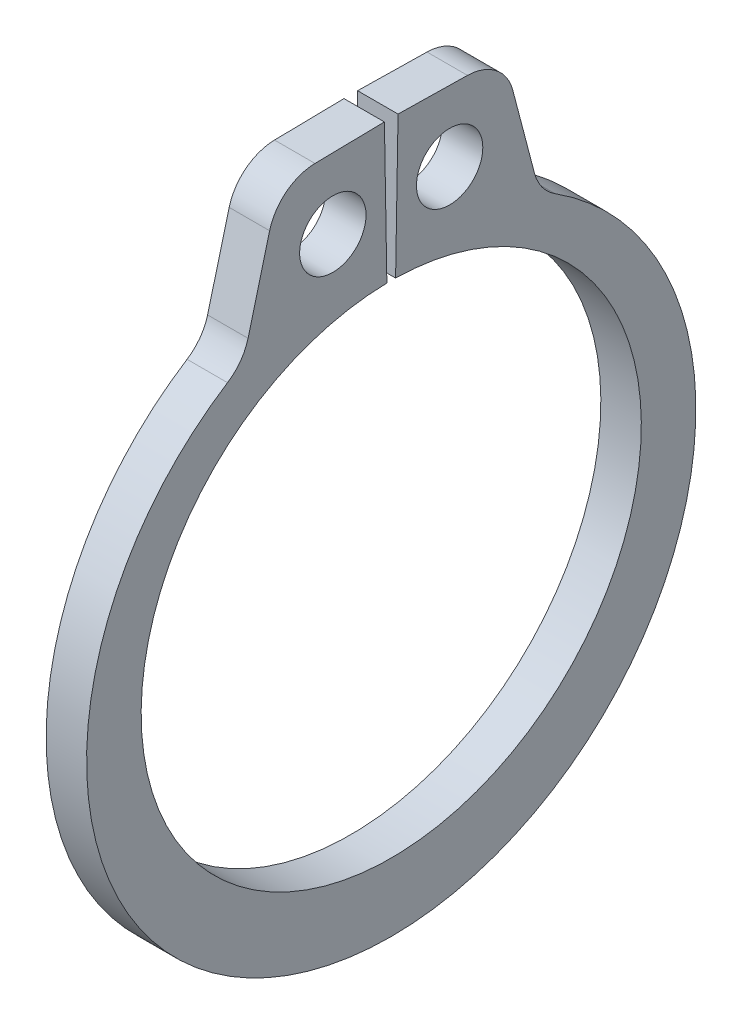
SolidWorks part; units mm, degrees
material "Cast Carbon Steel"
ref_plane "Front" through (0, 0, 0) normal (0, 0, 1) x (1, 0, 0)
ref_plane "Top" through (0, 0, 0) normal (0, 1, 0) x (1, 0, 0)
ref_plane "Right" through (0, 0, 0) normal (1, 0, 0) x (0, 0, -1)
sketch "Sketch1" plane through (0, 0, 0) normal (1, 0, 0) x (0, 0, -1)
  line L0 (0, 0) -> (0, 3.9243) construction
  line L1 (-0.0685, 3.9237) -> (-0.1071, 6.1332)
  line L2 (0.1071, 6.1332) -> (1.7642, 6.1042)
  line L3 (1.7642, 6.1042) -> (2.3243, 3.9666)
  line L4 (0.0685, 3.9237) -> (0.1071, 6.1332)
  line L5 (-0.1071, 6.1332) -> (-1.7642, 6.1042)
  line L6 (-1.7642, 6.1042) -> (-2.3243, 3.9666)
  line L7 (-2.3243, 3.9666) -> (-1.984, 3.3859) construction
  line L8 (2.3243, 3.9666) -> (1.984, 3.3859) construction
  line L9 (0, -3.9243) -> (0, -4.9911) construction
  line L10 (-1.7642, 6.1042) -> (-0.0685, 3.9237) construction
  line L11 (0, 3.9243) -> (0, 6.1341) construction
  line L12 (-3.9243, 0) -> (3.9243, 0) construction
  circle A0 centre (0, 0) radius 3.9243 construction
  arc A1 (-0.0685, 3.9237) -> (0.0685, 3.9237) centre (0, 0) ccw
  circle A3 centre (0, 0) radius 7.112 construction
  circle A4 centre (-0.9163, 5.014) radius 0.5207
  circle A5 centre (0.9163, 5.014) radius 0.5207
  arc A6 (-2.3243, 3.9666) -> (2.3243, 3.9666) centre (0, -0.2107) ccw
  point P0 (0, -4.9911)
  dimension "A" = 7.8486
  dimension "D2" = 1.6573
  dimension "L" = 14.224
  dimension "Hole" = 1.0414
  dimension "Smin" = 0.6731
  dimension "Smax" = 1.0668
  dimension "H" = 2.2098
  dimension "Angle" = 1
extrude "Extrude1" add sketch "Sketch1" along normal mid plane 0.635
fillet "Fillet1" radius 0.7493 4 edges at (0, 3.9666, 2.3243) (0, 3.9666, -2.3243) (0, 6.1042, 1.7642) (0, 6.1042, -1.7642)
sketch "Sketch2" plane through (0, 0, 0) normal (0, 0, 1) x (1, 0, 0)
  line L0 (-3.5433, 0) -> (9.1567, 0)
  line L1 (9.1567, 0) -> (9.1567, -4.3688)
  line L2 (-0.3683, -4.3688) -> (-3.2512, -4.3688)
  line L3 (9.1567, -4.3688) -> (0.3683, -4.3688)
  line L4 (0.3683, -4.3688) -> (0.3683, -4.0767)
  line L5 (0.3683, -4.0767) -> (-0.3683, -4.0767)
  line L6 (-0.3683, -4.0767) -> (-0.3683, -4.3688)
  line L7 (-0.3683, -4.3688) -> (-3.5433, -4.3688) construction
  line L8 (-3.5433, -4.3688) -> (-3.5433, 0) construction
  line L9 (9.1567, 0) -> (76.391, 0) construction
  line L10 (-3.2512, -4.3688) -> (-3.5433, -4.0767)
  line L11 (-3.5433, -4.0767) -> (-3.5433, 0)
  point P10 (0, -4.0767)
  dimension "D1" = 45
  dimension "Dg" = 8.1534
  dimension "Ds" = 8.7376
  dimension "W" = 0.7366
  dimension "D2" = 12.7
  dimension "D3" = 3.175
revolve "Revolve1" [suppressed] add sketch "Sketch2" angle 360 about L9
delete or keep bodies "Body-Delete1" [suppressed] type delete bodies bodies 122
equation "\"D2@Sketch2\" = \"D1@Extrude1\"*20"
equation "\"D3@Sketch2\" = \"D2@Sketch2\"/4"
equation "\"D2@Sketch1\" = \"H@Sketch1\"*.75"
